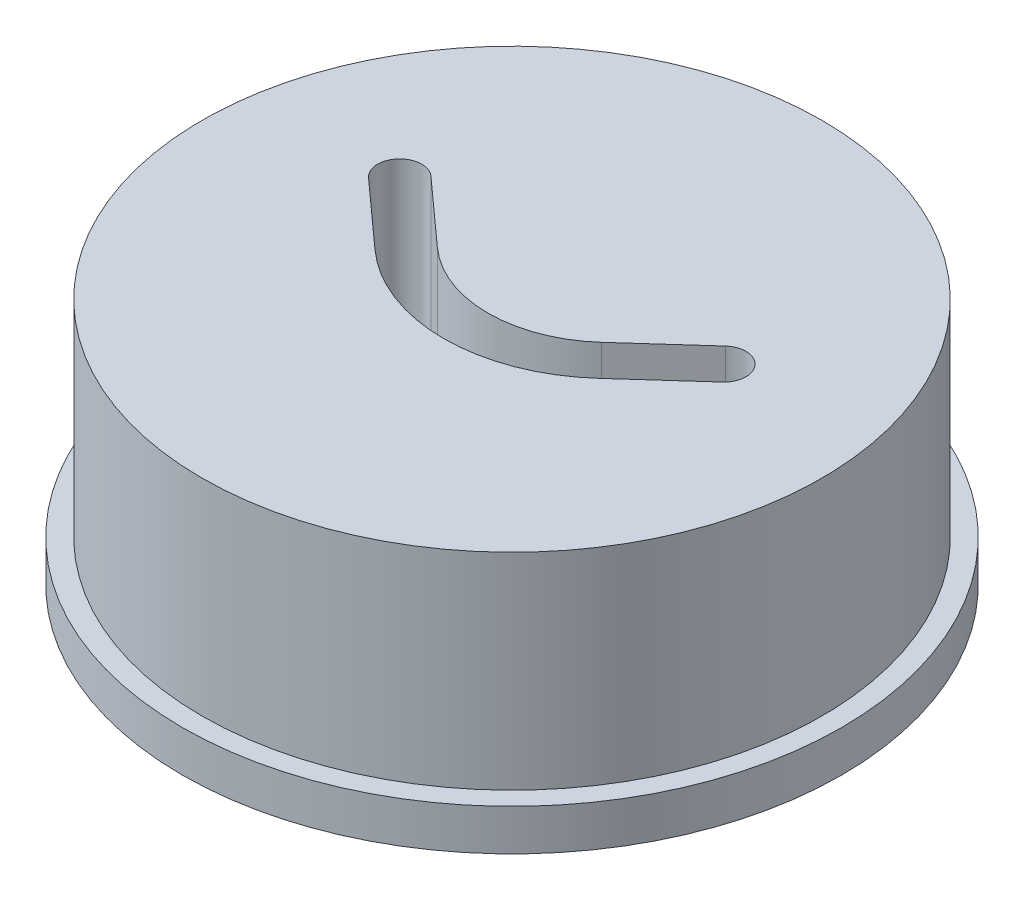
SolidWorks part; units mm, degrees
ref_plane "Front Plane" through (0, 0, 0) normal (0, 0, 1) x (1, 0, 0)
ref_plane "Top Plane" through (0, 0, 0) normal (0, 1, 0) x (1, 0, 0)
ref_plane "Right Plane" through (0, 0, 0) normal (1, 0, 0) x (0, 0, -1)
sketch "Sketch2" plane through (0, 0, 0) normal (0, 1, 0) x (1, 0, 0)
  line L0 (-6.985, 0) -> (6.985, 0) construction
  line L1 (10.6349, 10.6986) -> (16.7308, 17.0336) construction
  line L4 (-6.985, 6.985) -> (-6.985, -6.985) construction
  line L5 (-6.985, -6.985) -> (6.985, -6.985) construction
  line L6 (6.985, -6.985) -> (6.985, 6.985) construction
  line L7 (6.985, 6.985) -> (-6.985, 6.985) construction
  line L10 (0, 6.985) -> (0, -6.985) construction
  line L13 (0, -6.985) -> (0, 0) construction
  line L14 (-13.081, 3.175) -> (13.081, 3.175) construction
  line L15 (0, -4.445) -> (0, 3.175) construction
  line L16 (-13.081, 3.175) -> (-8.0591, -1.3498)
  line L17 (13.081, 3.175) -> (8.0591, -1.3498)
  line L18 (-11.8908, 4.4959) -> (-6.8689, -0.0289)
  line L19 (11.8908, 4.4959) -> (6.8689, -0.0289)
  line L21 (-12.4859, 3.8355) -> (12.4859, 3.8355) construction
  circle A0 centre (0, 0) radius 23.876
  arc A9 (-8.0591, -1.3498) -> (8.0591, -1.3498) centre (0, 7.5946) ccw
  arc A10 (-13.081, 3.175) -> (-11.8908, 4.4959) centre (-12.4859, 3.8355) cw
  arc A11 (-6.8689, -0.0289) -> (6.8689, -0.0289) centre (0, 7.5946) ccw
  arc A12 (11.8908, 4.4959) -> (13.081, 3.175) centre (12.4859, 3.8355) cw
  point P13 (16.7308, 17.0336)
  point P14 (10.6349, 10.6986)
  point P36 (0, 3.175)
  point P37 (-33.8663, 15.7634)
  point P42 (0, -4.445)
  point P47 (0, 3.175)
  dimension "D1" = 47.752
  dimension "D2" = 13.97
  dimension "D4" = 24.9718
  dimension "D9" = 12.0396
  dimension "D11" = 0.889
  dimension "D12" = 10.2616
  dimension "D3" = 3.175
  dimension "D10" = 6.7597
extrude "Boss-Extrude1" add sketch "Sketch2" along normal blind 19.05
sketch "Sketch14" plane through (0, 19.05, 0) normal (0, 1, 0) x (1, 0, 0)
  line L37 (8.6032, -1.9537) -> (13.6251, 2.5712)
  line L38 (11.3468, 5.0997) -> (6.3249, 0.5749)
  line L39 (-6.3249, 0.5749) -> (-11.3468, 5.0997)
  line L40 (-13.6251, 2.5712) -> (-8.6032, -1.9537)
  line L41 (8.6032, -1.9537) -> (13.6251, 2.5712)
  line L42 (11.3468, 5.0997) -> (6.3249, 0.5749)
  line L43 (-6.3249, 0.5749) -> (-11.3468, 5.0997)
  line L44 (-13.6251, 2.5712) -> (-8.6032, -1.9537)
  arc A43 (13.6251, 2.5712) -> (11.3468, 5.0997) centre (12.4859, 3.8355) ccw
  arc A44 (-6.3249, 0.5749) -> (6.3249, 0.5749) centre (0, 7.5946) ccw
  arc A45 (-11.3468, 5.0997) -> (-13.6251, 2.5712) centre (-12.4859, 3.8355) ccw
  arc A46 (-8.6032, -1.9537) -> (8.6032, -1.9537) centre (0, 7.5946) ccw
  arc A47 (13.6251, 2.5712) -> (11.3468, 5.0997) centre (12.4859, 3.8355) ccw
  arc A48 (-6.3249, 0.5749) -> (6.3249, 0.5749) centre (0, 7.5946) ccw
  arc A49 (-11.3468, 5.0997) -> (-13.6251, 2.5712) centre (-12.4859, 3.8355) ccw
  arc A50 (-8.6032, -1.9537) -> (8.6032, -1.9537) centre (0, 7.5946) ccw
  dimension "D1" = 0.8128
extrude "Cut-Extrude2" cut sketch "Sketch14" against normal blind 12.7
sketch "Sketch15" plane through (0, 0, 0) normal (0, -1, 0) x (1, 0, 0)
  line L0 (-6.8689, 0.0289) -> (-11.8908, -4.4959) construction
  line L1 (-13.081, -3.175) -> (-8.0591, 1.3498) construction
  line L2 (11.8908, -4.4959) -> (6.8689, 0.0289) construction
  line L3 (8.0591, 1.3498) -> (13.081, -3.175) construction
  line L4 (-6.8689, 0.0289) -> (-11.8908, -4.4959)
  line L5 (-13.081, -3.175) -> (-8.0591, 1.3498)
  line L6 (11.8908, -4.4959) -> (6.8689, 0.0289)
  line L7 (8.0591, 1.3498) -> (13.081, -3.175)
  circle A0 centre (0, 0) radius 25.4
  arc A1 (6.8689, 0.0289) -> (-6.8689, 0.0289) centre (0, -7.5946) ccw construction
  arc A2 (-13.081, -3.175) -> (-11.8908, -4.4959) centre (-12.4859, -3.8355) ccw construction
  arc A3 (8.0591, 1.3498) -> (-8.0591, 1.3498) centre (0, -7.5946) ccw construction
  arc A4 (11.8908, -4.4959) -> (13.081, -3.175) centre (12.4859, -3.8355) ccw construction
  arc A5 (6.8689, 0.0289) -> (-6.8689, 0.0289) centre (0, -7.5946) ccw
  arc A6 (-13.081, -3.175) -> (-11.8908, -4.4959) centre (-12.4859, -3.8355) ccw
  arc A7 (8.0591, 1.3498) -> (-8.0591, 1.3498) centre (0, -7.5946) ccw
  arc A8 (11.8908, -4.4959) -> (13.081, -3.175) centre (12.4859, -3.8355) ccw
  dimension "D1" = 50.8
extrude "Boss-Extrude2" add sketch "Sketch15" against normal blind 3.175
